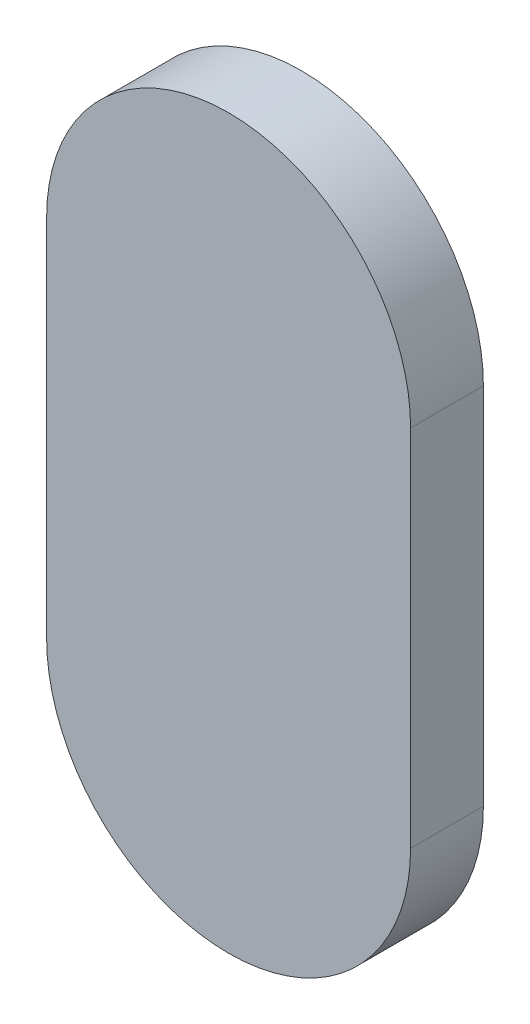
SolidWorks part; units mm, degrees
ref_plane "Спереди" through (0, 0, 0) normal (0, 0, 1) x (1, 0, 0)
ref_plane "Сверху" through (0, 0, 0) normal (0, 1, 0) x (1, 0, 0)
ref_plane "Справа" through (0, 0, 0) normal (1, 0, 0) x (0, 0, -1)
other "Configuration Table"
sketch "Эскиз2" plane through (0, 0, 0) normal (0, 0, 1) x (1, 0, 0)
  line L0 (0, 25) -> (0, -25) construction
  line L2 (25, 25) -> (25, -25)
  line L3 (-25, 25) -> (-25, -25)
  arc A0 (25, 25) -> (-25, 25) centre (0, 25) ccw
  arc A1 (-25, -25) -> (25, -25) centre (0, -25) ccw
  point P3 (0, -50)
  point P4 (0, 50)
  point P5 (0, 0)
  point P10 (0, 0)
  point P11 (0, 0)
  dimension "D2" = 50
  dimension "D1" = 100
extrude "Бобышка-Вытянуть1" add sketch "Эскиз2" along normal blind 10
